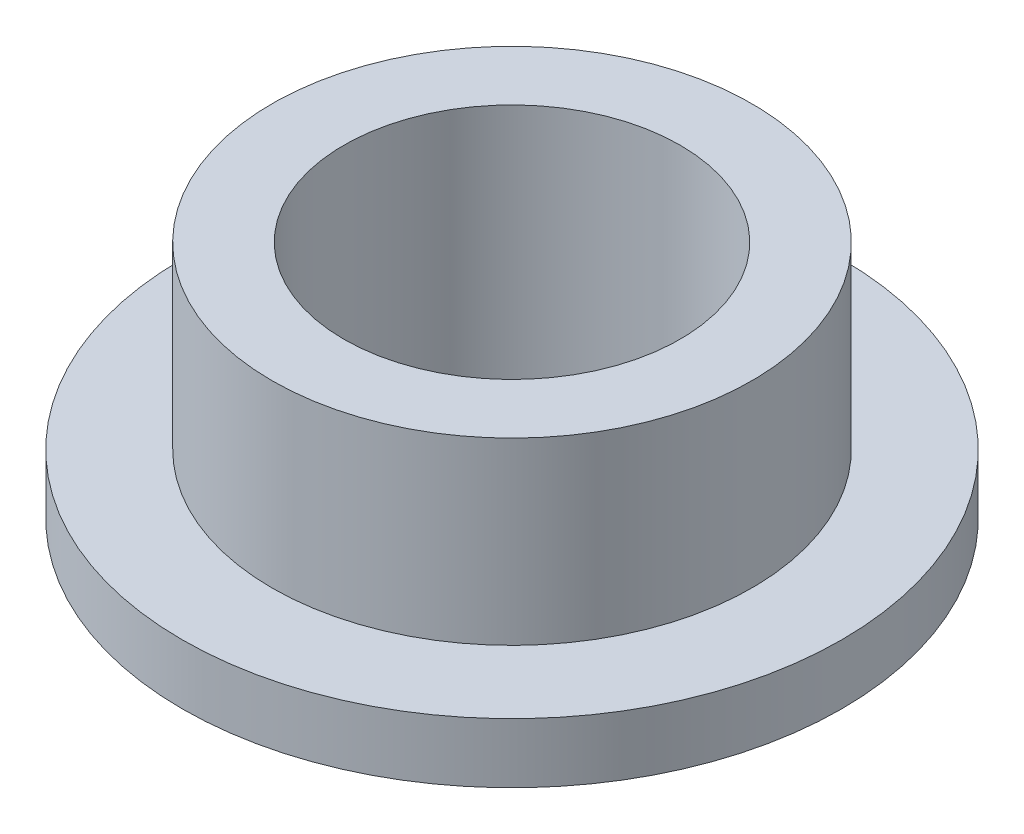
SolidWorks part; units mm, degrees
ref_plane "Front Plane" through (0, 0, 0) normal (0, 0, 1) x (1, 0, 0)
ref_plane "Top Plane" through (0, 0, 0) normal (0, 1, 0) x (1, 0, 0)
ref_plane "Right Plane" through (0, 0, 0) normal (1, 0, 0) x (0, 0, -1)
sketch "Sketch1" plane through (0, 0, 0) normal (0, 1, 0) x (1, 0, 0)
  circle A0 centre (0, 0) radius 20.05
  circle A1 centre (0, 0) radius 14.05
  dimension "D1" = 40.1
  dimension "D2" = 28.1
extrude "Boss-Extrude1" add sketch "Sketch1" along normal blind 15
sketch "Sketch2" plane through (0, 0, 0) normal (0, 1, 0) x (1, 0, 0)
  circle A0 centre (0, 0) radius 14.05
  circle A1 centre (0, 0) radius 27.55
  dimension "D1" = 28.1
  dimension "D2" = 55.1
extrude "Boss-Extrude2" add sketch "Sketch2" against normal blind 5
